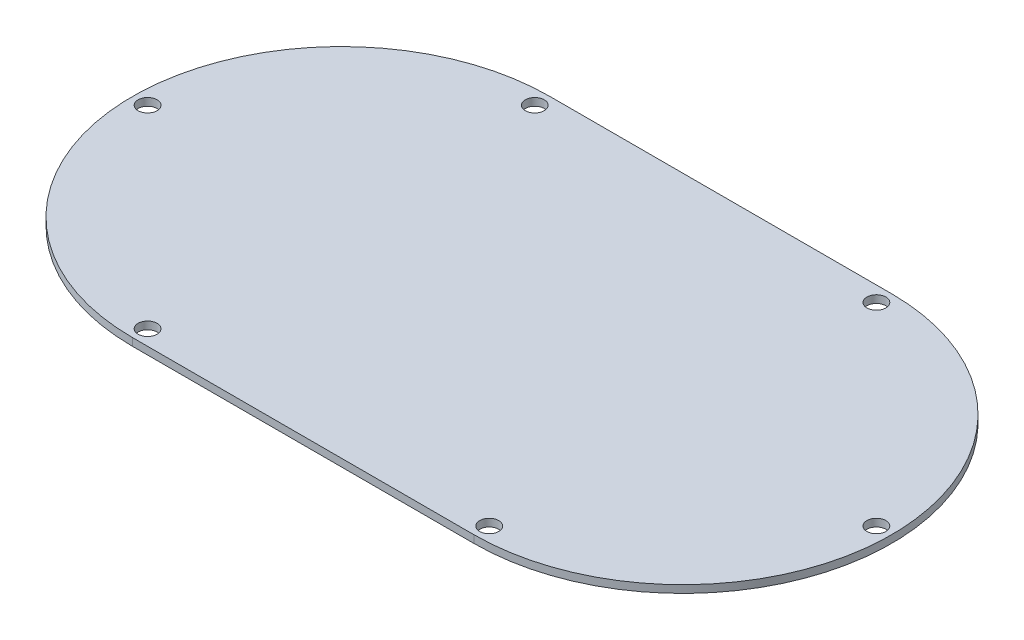
SolidWorks part; units mm, degrees
ref_plane "前视基准面" through (0, 0, 0) normal (0, 0, 1) x (1, 0, 0)
ref_plane "上视基准面" through (0, 0, 0) normal (0, 1, 0) x (1, 0, 0)
ref_plane "右视基准面" through (0, 0, 0) normal (1, 0, 0) x (0, 0, -1)
other "Configuration Table"
sketch "草图1" plane through (0, 0, 0) normal (0, 1, 0) x (1, 0, 0)
  line L0 (0, 63.3099) -> (0, -105.9699) construction
  line L1 (-45, 0) -> (45, 0) construction
  line L2 (-45, 55) -> (45, 55)
  line L3 (-45, -55) -> (45, -55)
  arc A0 (-45, 55) -> (-45, -55) centre (-45, 0) ccw
  arc A1 (45, -55) -> (45, 55) centre (45, 0) ccw
  circle A2 centre (-45, 51) radius 2.5
  circle A3 centre (-96, 0) radius 2.5
  circle A4 centre (-45, -51) radius 2.5
  circle A5 centre (45, -51) radius 2.5
  circle A6 centre (96, 0) radius 2.5
  circle A7 centre (45, 51) radius 2.5
  point P5 (0, 0)
  point P14 (0, 0)
  point P15 (0, 0)
  dimension "D1" = 90
  dimension "D2" = 200
  dimension "D3" = 5
  dimension "D4" = 102
  dimension "D5" = 192
extrude "凸台-拉伸1" add sketch "草图1" along normal blind 2
